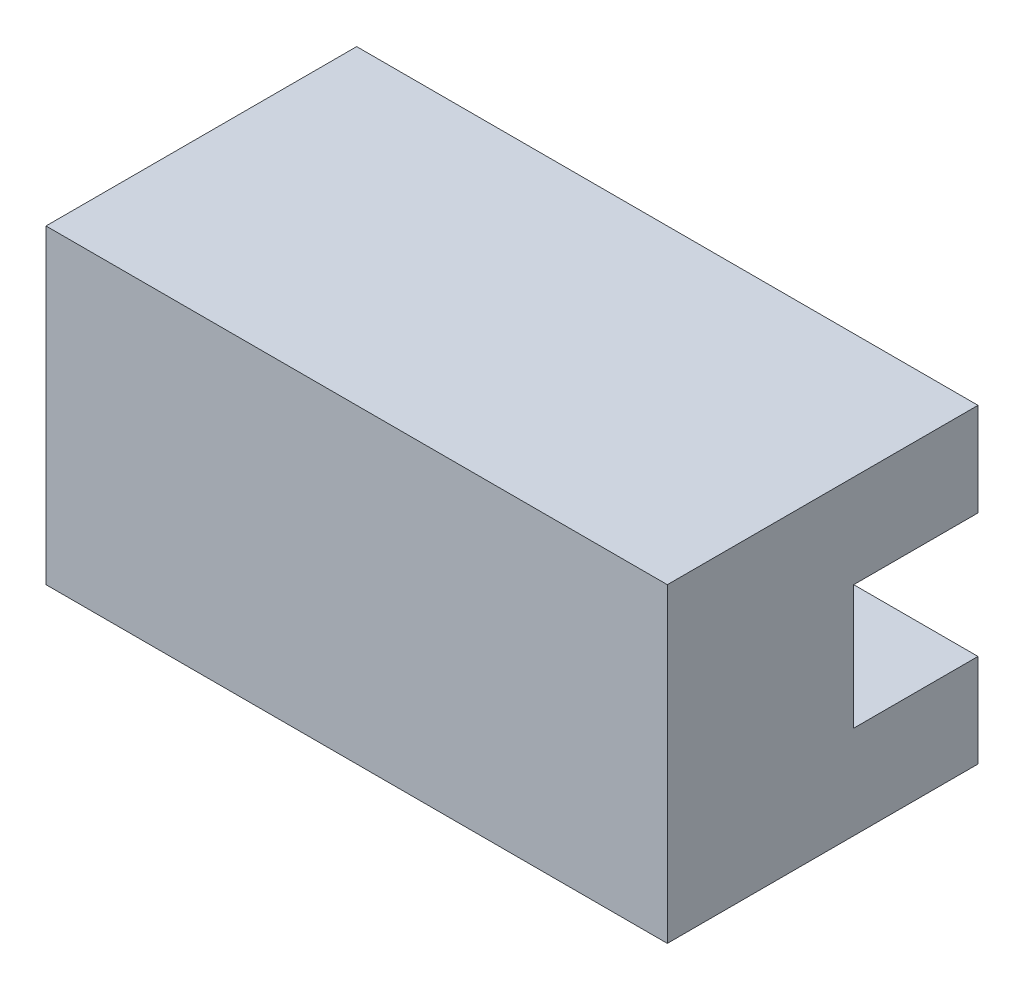
SolidWorks part; units mm, degrees
ref_plane "Front Plane" through (0, 0, 0) normal (0, 0, 1) x (1, 0, 0)
ref_plane "Top Plane" through (0, 0, 0) normal (0, 1, 0) x (1, 0, 0)
ref_plane "Right Plane" through (0, 0, 0) normal (1, 0, 0) x (0, 0, -1)
sketch "Sketch1" plane through (0, 0, 0) normal (0, 1, 0) x (1, 0, 0)
  line L1 (-100, -50) -> (100, -50)
  line L2 (-100, -50) -> (-100, 50)
  line L3 (-100, 50) -> (100, 50)
  line L4 (100, -50) -> (100, 50)
  line L5 (-100, -50) -> (100, 50) construction
  line L6 (-100, 50) -> (100, -50) construction
  point P0 (0, 0)
  dimension "D1" = 200
  dimension "D2" = 100
extrude "Boss-Extrude1" add sketch "Sketch1" along normal blind 100
sketch "Sketch3" plane through (100, 0, 0) normal (1, 0, 0) x (0, 0, -1)
  line L5 (50, 100) -> (50, 0) construction
  line L6 (50, 70) -> (10, 70)
  line L7 (50, 70) -> (50, 30)
  line L8 (50, 30) -> (10, 30)
  line L9 (10, 70) -> (10, 30)
  line L10 (-50, 100) -> (50, 100) construction
  dimension "D1" = 40
  dimension "D2" = 40
  dimension "D3" = 30
extrude "Cut-Extrude1" cut sketch "Sketch3" against normal blind 200
